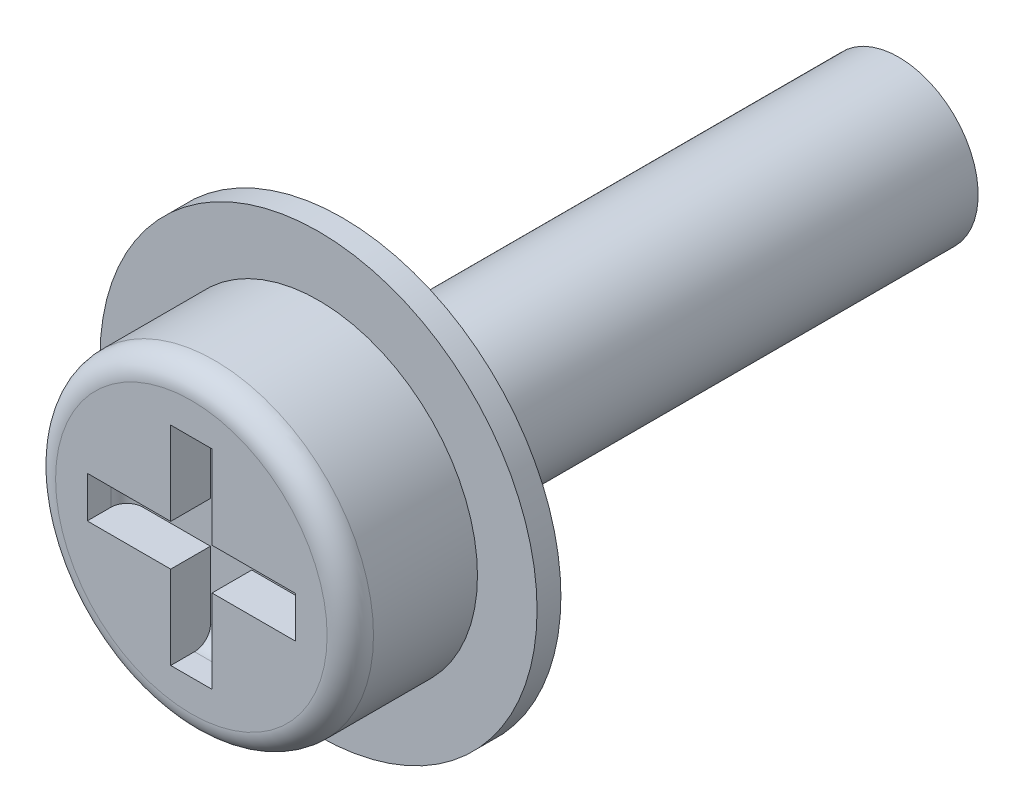
SolidWorks part; units mm, degrees
ref_plane "Plan de face" through (0, 0, 0) normal (0, 0, 1) x (1, 0, 0)
ref_plane "Plan de dessus" through (0, 0, 0) normal (0, 1, 0) x (1, 0, 0)
ref_plane "Plan de droite" through (0, 0, 0) normal (1, 0, 0) x (0, 0, -1)
sketch "Esquisse1" plane through (0, 0, 0) normal (0, 0, 1) x (1, 0, 0)
  circle A0 centre (0, 0) radius 3.3
  dimension "D1" = 6.6
extrude "Boss.-Extru.1" add sketch "Esquisse1" along normal blind 0.36
sketch "Esquisse2" plane through (0, 0, 0.36) normal (0, 0, 1) x (1, 0, 0)
  circle A0 centre (0, 0) radius 2.4
  dimension "D1" = 4.8
extrude "Boss.-Extru.2" add sketch "Esquisse2" along normal blind 1.92
sketch "Esquisse3" plane through (0, 0, 0) normal (0, 0, -1) x (-1, 0, 0)
  circle A0 centre (0, 0) radius 1.2
  dimension "D1" = 2.4
extrude "Boss.-Extru.3" add sketch "Esquisse3" along normal blind 8.4
fillet "Congé1" radius 0.35 1 edges at (2.4, 0, 2.28)
sketch "Esquisse4" plane through (0, 0, 2.28) normal (0, 0, 1) x (1, 0, 0)
  line L0 (0, 3.3862) -> (0, -4.1736) construction
  line L1 (-2.6249, 0) -> (3.6224, 0) construction
  line L2 (-1.572, -0.312) -> (-1.572, 0.312)
  line L3 (-1.572, 0.312) -> (-0.312, 0.312)
  line L4 (-0.312, 0.312) -> (-0.312, 1.572)
  line L5 (-0.312, 1.572) -> (0.312, 1.572)
  line L6 (-1.572, -0.312) -> (-0.312, -0.312)
  line L7 (-0.312, -0.312) -> (-0.312, -1.572)
  line L8 (-0.312, -1.572) -> (0.312, -1.572)
  line L9 (0.312, -0.312) -> (0.312, -1.572)
  line L10 (1.572, -0.312) -> (0.312, -0.312)
  line L11 (1.572, -0.312) -> (1.572, 0.312)
  line L12 (1.572, 0.312) -> (0.312, 0.312)
  line L13 (0.312, 0.312) -> (0.312, 1.572)
  point P11 (-1.572, 0)
  point P15 (0, -1.572)
  point P20 (0, 1.572)
  dimension "D1" = 1.26
  dimension "D2" = 1.26
  dimension "D3" = 0.312
  dimension "D4" = 0.312
  dimension "D5" = 3.144
  dimension "D6" = 0.624
  dimension "D7" = 1.26
extrude "Enlèv. mat.-Extru.1" cut sketch "Esquisse4" against normal blind 0.6
fillet "Congé2" radius 0.24 4 edges at (0, -1.572, 1.68) (-1.572, 0, 1.68) (1.572, 0, 1.68) (0, 1.572, 1.68)
